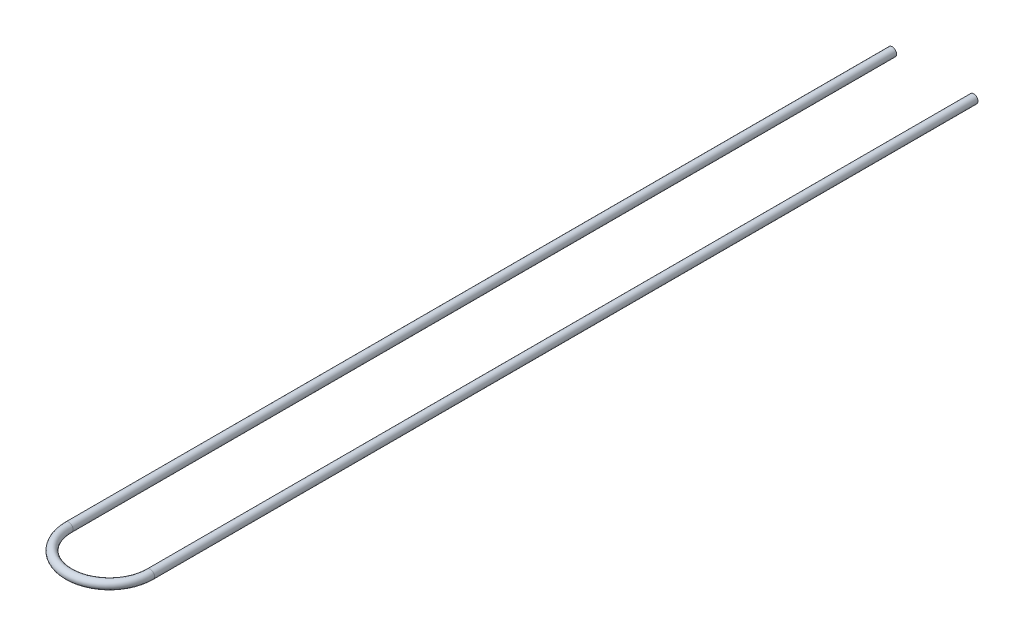
SolidWorks part; units mm, degrees
ref_plane "Front Plane" through (0, 0, 0) normal (0, 0, 1) x (1, 0, 0)
ref_plane "Top Plane" through (0, 0, 0) normal (0, 1, 0) x (1, 0, 0)
ref_plane "Right Plane" through (0, 0, 0) normal (1, 0, 0) x (0, 0, -1)
sketch "Sketch1" plane through (0, 0, 0) normal (0, 1, 0) x (1, 0, 0)
  line L0 (171.69, -300) -> (171.69, -2440)
  line L2 (-40, -300) -> (-40, -2440)
  arc A0 (-40, -2440) -> (171.69, -2440) centre (65.845, -2440) ccw
  dimension "D1" = 2140
  dimension "D2" = 211.69
ref_plane "Plane1" through (171.69, 0, 300) normal (0, 0, -1) x (-1, 0, 0)
sketch "Sketch2" plane through (171.69, 0, 300) normal (0, 0, -1) x (-1, 0, 0)
  circle A0 centre (0, 0) radius 9.95
  circle A1 centre (0, 0) radius 11.1
  dimension "D1" = 22.2
  dimension "D2" = 19.9
sweep "Sweep1" add profiles "Sketch2" path "Sketch1"
